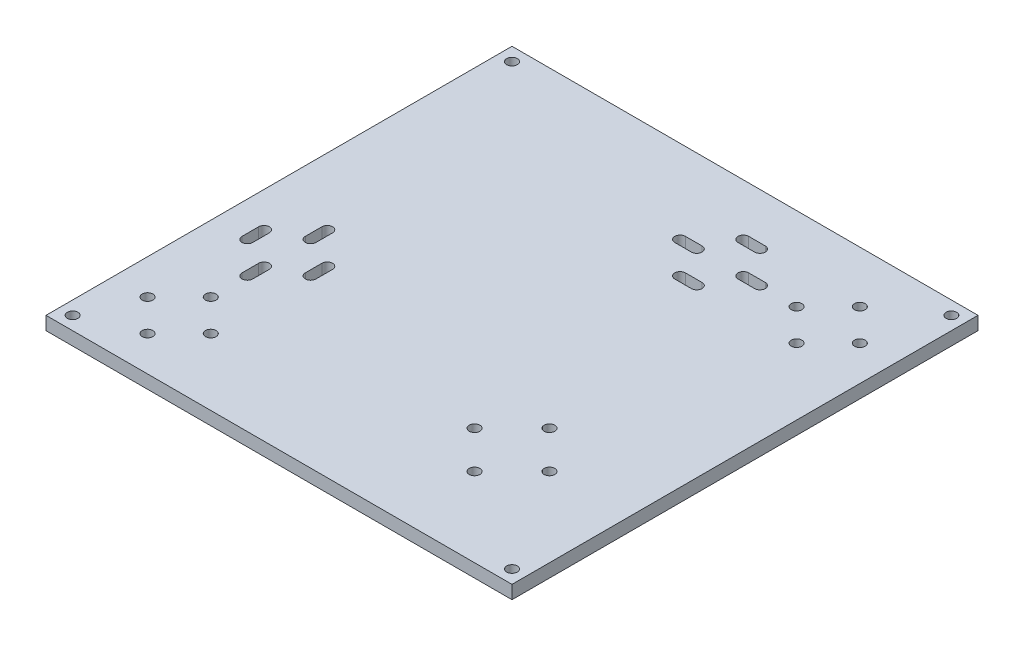
SolidWorks part; units mm, degrees
ref_plane "前视基准面" through (0, 0, 0) normal (0, 0, 1) x (1, 0, 0)
ref_plane "上视基准面" through (0, 0, 0) normal (0, 1, 0) x (1, 0, 0)
ref_plane "右视基准面" through (0, 0, 0) normal (1, 0, 0) x (0, 0, -1)
sketch "Sketch1" plane through (0, 0, 0) normal (0, 1, 0) x (1, 0, 0)
  line L1 (-70, 70) -> (70, 70)
  line L2 (-70, 70) -> (-70, -70)
  line L3 (-70, -70) -> (70, -70)
  line L4 (70, 70) -> (70, -70)
  line L5 (0, -70) -> (0, 70) construction
  line L6 (-70, 0) -> (70, 0) construction
  point P0 (0, 0)
  dimension "D1" = 140
  dimension "D2" = 140
extrude "Boss-Extrude1" add sketch "Sketch1" along normal blind 4
sketch "Sketch2" plane through (0, 4, 0) normal (0, 1, 0) x (1, 0, 0)
  line L0 (70, -70) -> (70, 70) construction
  line L1 (70, 70) -> (-70, 70) construction
  line L2 (-70, -70) -> (70, -70) construction
  line L3 (-70, 70) -> (-70, -70) construction
  line L4 (20, 45) -> (29.5, 45) construction
  line L5 (-50, -20) -> (-50, -29.5) construction
  line L6 (50, 45) -> (59.5, 45) construction
  line L8 (-50, -50) -> (-50, -59.5) construction
  circle A0 centre (50, 45) radius 14 construction
  circle A1 centre (20, 45) radius 14 construction
  circle A2 centre (-50, -20) radius 14 construction
  circle A3 centre (-50, -50) radius 14 construction
  circle A5 centre (29.5, 45) radius 1.6
  circle A6 centre (59.5, 45) radius 1.6
  circle A7 centre (-50, -29.5) radius 1.6
  circle A8 centre (-50, -59.5) radius 1.6
  circle A9 centre (20, 35.5) radius 1.6
  circle A10 centre (10.5, 45) radius 1.6
  circle A11 centre (20, 54.5) radius 1.6
  circle A12 centre (50, 35.5) radius 1.6
  circle A13 centre (40.5, 45) radius 1.6
  circle A14 centre (50, 54.5) radius 1.6
  circle A15 centre (-59.5, -50) radius 1.6
  circle A16 centre (-50, -40.5) radius 1.6
  circle A17 centre (-40.5, -50) radius 1.6
  circle A19 centre (-59.5, -20) radius 1.6
  circle A21 centre (-50, -10.5) radius 1.6
  circle A23 centre (-40.5, -20) radius 1.6
  circle A24 centre (-10.5, -20) radius 1.6 [skipped]
  circle A25 centre (-89.5, -20) radius 1.6 [skipped]
  circle A26 centre (-50, 19.5) radius 1.6 [skipped]
  point P33 (20, 45)
  point P40 (50, 45)
  point P47 (-50, -50)
  point P60 (-50, -20)
  dimension "D1" = 28
  dimension "D8" = 3.2
  dimension "D11" = 3.2
  dimension "D2" = 20
  dimension "D3" = 25
  dimension "D4" = 20
  dimension "D5" = 20
  dimension "D6" = 30
  dimension "D7" = 30
  dimension "D9" = 9.5
  dimension "D10" = 9.5
  dimension "D12" = 9.5
  dimension "D13" = 4
  dimension "D14" = 4
  dimension "D15" = 4
  dimension "D16" = 4
extrude "Cut-Extrude1" cut sketch "Sketch2" against normal blind 4
sketch "Sketch3" plane through (0, 4, 0) normal (0, 1, 0) x (1, 0, 0)
  line L0 (-50, -29.5) -> (-50, -40.5) construction
  line L2 (29.5, 45) -> (40.5, 45) construction
  line L4 (-50, -35) -> (35, -35) construction
  line L5 (35, -35) -> (35, 45) construction
  circle A0 centre (35, -35) radius 16.8 construction
  circle A1 centre (35, -23.75) radius 1.6
  circle A2 centre (46.25, -35) radius 1.6
  circle A3 centre (35, -46.25) radius 1.6
  circle A4 centre (23.75, -35) radius 1.6
  point P23 (35, -35)
  dimension "D1" = 33.6
  dimension "D2" = 11.25
  dimension "D3" = 3.2
  dimension "D4" = 4
extrude "Cut-Extrude2" cut sketch "Sketch3" against normal blind 10
sketch "Sketch4" plane through (0, 4, 0) normal (0, 1, 0) x (1, 0, 0)
  line L0 (-50, -29.5) -> (-50, -24.5) construction
  line L1 (-51.6, -29.5) -> (-51.6, -24.5)
  line L2 (-48.4, -29.5) -> (-48.4, -24.5)
  line L3 (-40.5, -20) -> (-40.5, -15) construction
  line L4 (-42.1, -20) -> (-42.1, -15)
  line L5 (-38.9, -20) -> (-38.9, -15)
  line L6 (-50, -10.5) -> (-50, -5.5) construction
  line L7 (-51.6, -10.5) -> (-51.6, -5.5)
  line L8 (-48.4, -10.5) -> (-48.4, -5.5)
  line L9 (-59.5, -20) -> (-59.5, -15) construction
  line L10 (-61.1, -20) -> (-61.1, -15)
  line L11 (-57.9, -20) -> (-57.9, -15)
  line L12 (10.5, 45) -> (5.5, 45) construction
  line L13 (10.5, 43.4) -> (5.5, 43.4)
  line L14 (10.5, 46.6) -> (5.5, 46.6)
  line L15 (20, 54.5) -> (15, 54.5) construction
  line L16 (20, 52.9) -> (15, 52.9)
  line L17 (20, 56.1) -> (15, 56.1)
  line L18 (29.5, 45) -> (24.5, 45) construction
  line L19 (29.5, 43.4) -> (24.5, 43.4)
  line L20 (29.5, 46.6) -> (24.5, 46.6)
  line L21 (20, 35.5) -> (15, 35.5) construction
  line L22 (20, 33.9) -> (15, 33.9)
  line L23 (20, 37.1) -> (15, 37.1)
  arc A0 (-51.6, -29.5) -> (-48.4, -29.5) centre (-50, -29.5) ccw
  arc A1 (-48.4, -24.5) -> (-51.6, -24.5) centre (-50, -24.5) ccw
  arc A2 (-42.1, -20) -> (-38.9, -20) centre (-40.5, -20) ccw
  arc A3 (-38.9, -15) -> (-42.1, -15) centre (-40.5, -15) ccw
  arc A4 (-51.6, -10.5) -> (-48.4, -10.5) centre (-50, -10.5) ccw
  arc A5 (-48.4, -5.5) -> (-51.6, -5.5) centre (-50, -5.5) ccw
  arc A6 (-61.1, -20) -> (-57.9, -20) centre (-59.5, -20) ccw
  arc A7 (-57.9, -15) -> (-61.1, -15) centre (-59.5, -15) ccw
  arc A8 (10.5, 43.4) -> (10.5, 46.6) centre (10.5, 45) ccw
  arc A9 (5.5, 46.6) -> (5.5, 43.4) centre (5.5, 45) ccw
  arc A10 (20, 52.9) -> (20, 56.1) centre (20, 54.5) ccw
  arc A11 (15, 56.1) -> (15, 52.9) centre (15, 54.5) ccw
  arc A12 (29.5, 43.4) -> (29.5, 46.6) centre (29.5, 45) ccw
  arc A13 (24.5, 46.6) -> (24.5, 43.4) centre (24.5, 45) ccw
  arc A14 (20, 33.9) -> (20, 37.1) centre (20, 35.5) ccw
  arc A15 (15, 37.1) -> (15, 33.9) centre (15, 35.5) ccw
  circle A16 centre (29.5, 45) radius 1.6 construction
  point P3 (-50, -27)
  point P8 (-40.5, -17.5)
  point P16 (-50, -8)
  point P24 (-59.5, -17.5)
  point P32 (8, 45)
  point P40 (17.5, 54.5)
  point P48 (27, 45)
  point P56 (17.5, 35.5)
  dimension "D1" = 5
extrude "Cut-Extrude3" cut sketch "Sketch4" against normal blind 10
sketch "Sketch5" plane through (0, 4, 0) normal (0, 1, 0) x (1, 0, 0)
  line L0 (-70, -70) -> (70, -70) construction
  line L1 (-66, -66) -> (66, -66) construction
  line L2 (-66, -66) -> (-66, 66) construction
  line L3 (-66, 66) -> (66, 66) construction
  line L4 (66, -66) -> (66, 66) construction
  line L5 (0, 66) -> (0, -66) construction
  line L6 (-66, 0) -> (66, 0) construction
  line L7 (-70, 70) -> (-70, -70) construction
  circle A0 centre (-66, 66) radius 1.6
  circle A1 centre (66, 66) radius 1.6
  circle A2 centre (66, -66) radius 1.6
  circle A3 centre (-66, -66) radius 1.6
  point P0 (0, 0)
  dimension "D1" = 3.2
  dimension "D2" = 4
  dimension "D3" = 4
extrude "Cut-Extrude5" cut sketch "Sketch5" against normal blind 10
equation "\"D4@Sketch2\"=\"D5@Sketch2\""
equation "\"D2@Sketch2\"=\"D5@Sketch2\""
equation "\"D3@Sketch5\"=\"D2@Sketch5\""
